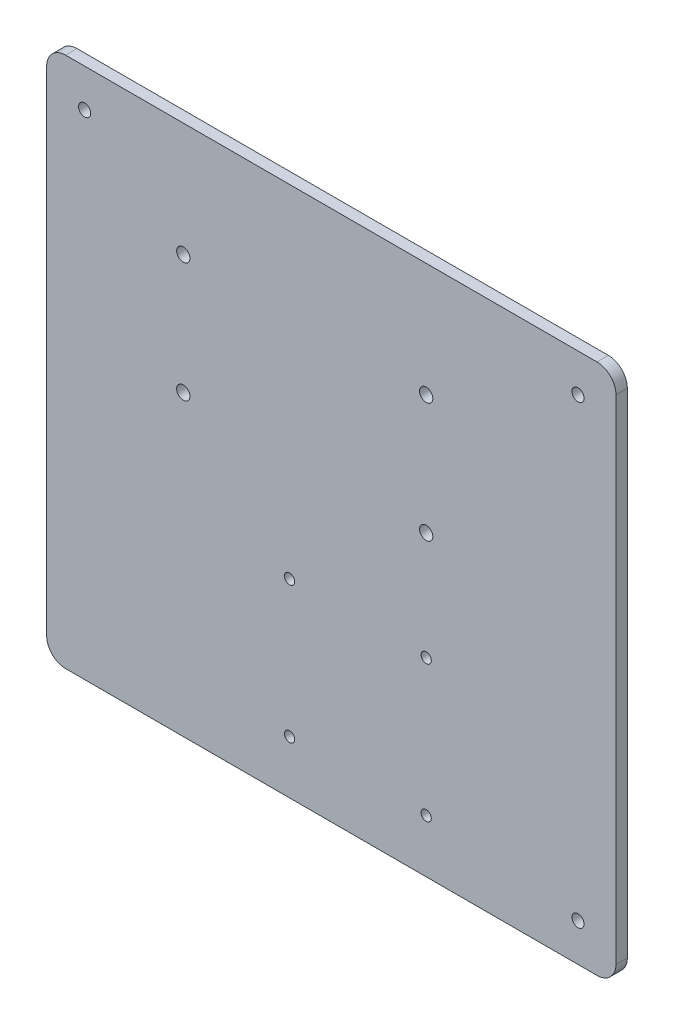
SolidWorks part; units mm, degrees
material "Thornel Mat VMA"
ref_plane "前视基准面" through (0, 0, 0) normal (0, 0, 1) x (1, 0, 0)
ref_plane "上视基准面" through (0, 0, 0) normal (0, 1, 0) x (1, 0, 0)
ref_plane "右视基准面" through (0, 0, 0) normal (1, 0, 0) x (0, 0, -1)
sketch "草图1" plane through (0, 0, 0) normal (0, 0, 1) x (1, 0, 0)
  line L1 (-75, 70) -> (75, 70)
  line L2 (-75, 70) -> (-75, -70)
  line L3 (-75, -70) -> (75, -70)
  line L4 (75, 70) -> (75, -70)
  line L5 (-75, 70) -> (75, -70) construction
  line L6 (-75, -70) -> (75, 70) construction
  point P0 (0, 0)
  dimension "D1" = 150
  dimension "D2" = 140
extrude "凸台-拉伸1" add sketch "草图1" along normal blind 3
sketch "草图3" plane through (0, 0, 3) normal (0, 0, 1) x (1, 0, 0)
  line L0 (75, 70) -> (-75, 70) construction
  line L1 (75, -70) -> (75, 70) construction
  circle A0 centre (25, 40) radius 1.75
  circle A3 centre (-39, 40) radius 1.75
  circle A4 centre (25, 8.5) radius 1.75
  circle A5 centre (-39, 8.5) radius 1.75
  dimension "D1" = 3.5
  dimension "D2" = 30
  dimension "D3" = 50
  dimension "D4" = 2
  dimension "D5" = 2
extrude "切除-拉伸1" cut sketch "草图3" against normal blind 10
sketch "草图4" plane through (0, 0, 3) normal (0, 0, 1) x (1, 0, 0)
  line L0 (75, -70) -> (75, 70) construction
  line L1 (-75, -70) -> (75, -70) construction
  circle A0 centre (25, -20) radius 1.35
  circle A1 centre (-11, -20) radius 1.35
  circle A2 centre (-11, -56) radius 1.35
  circle A3 centre (25, -56) radius 1.35
  dimension "D1" = 2.7
  dimension "D2" = 50
  dimension "D3" = 50
  dimension "D4" = 2
  dimension "D5" = 2
extrude "切除-拉伸2" cut sketch "草图4" against normal blind 10
sketch "草图5" plane through (0, 0, 3) normal (0, 0, 1) x (1, 0, 0)
  line L0 (75, 70) -> (-75, 70) construction
  line L1 (75, -70) -> (75, 70) construction
  circle A0 centre (65, 60) radius 1.6
  circle A1 centre (-65, 60) radius 1.6
  circle A3 centre (65, -60) radius 1.6
  circle A4 centre (-65, -60) radius 1.6 [skipped]
  dimension "D1" = 3.2
  dimension "D2" = 10
  dimension "D3" = 10
  dimension "D4" = 2
  dimension "D5" = 2
extrude "切除-拉伸3" cut sketch "草图5" against normal blind 10
fillet "圆角1" radius 5 4 edges at (-75, -70, 1.5) (75, -70, 1.5) (75, 70, 1.5) (-75, 70, 1.5)
